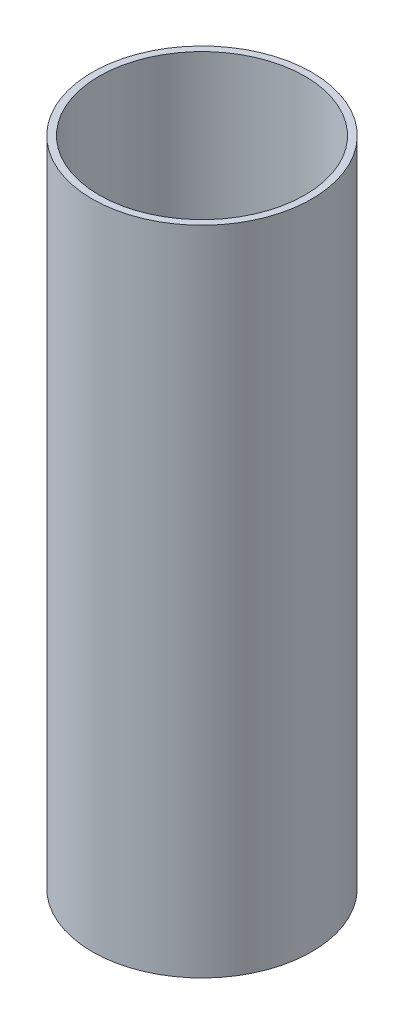
SolidWorks part; units mm, degrees
ref_plane "Спереди" through (0, 0, 0) normal (0, 0, 1) x (1, 0, 0)
ref_plane "Сверху" through (0, 0, 0) normal (0, 1, 0) x (1, 0, 0)
ref_plane "Справа" through (0, 0, 0) normal (1, 0, 0) x (0, 0, -1)
sketch "Sketch1" plane through (0, 0, 0) normal (0, 1, 0) x (1, 0, 0)
  circle A0 centre (0, 0) radius 16
  circle A1 centre (0, 0) radius 15
  dimension "D1" = 32
  dimension "D2" = 30
extrude "Boss-Extrude1" add sketch "Sketch1" along normal blind 85
ref_plane "Plane1" through (0, 0, -16) normal (0, 0, 1) x (1, 0, 0)
sketch "Sketch3" plane through (0, 0, -16) normal (0, 0, 1) x (1, 0, 0)
  line L0 (0, -17.2648) -> (0, 74.8033) construction
sketch "Sketch4" plane through (0, 0, 0) normal (0, 1, 0) x (1, 0, 0)
  circle A0 centre (0, 0) radius 16
  circle A1 centre (0, 0) radius 15
extrude "Boss-Extrude2" add sketch "Sketch4" against normal blind 10
